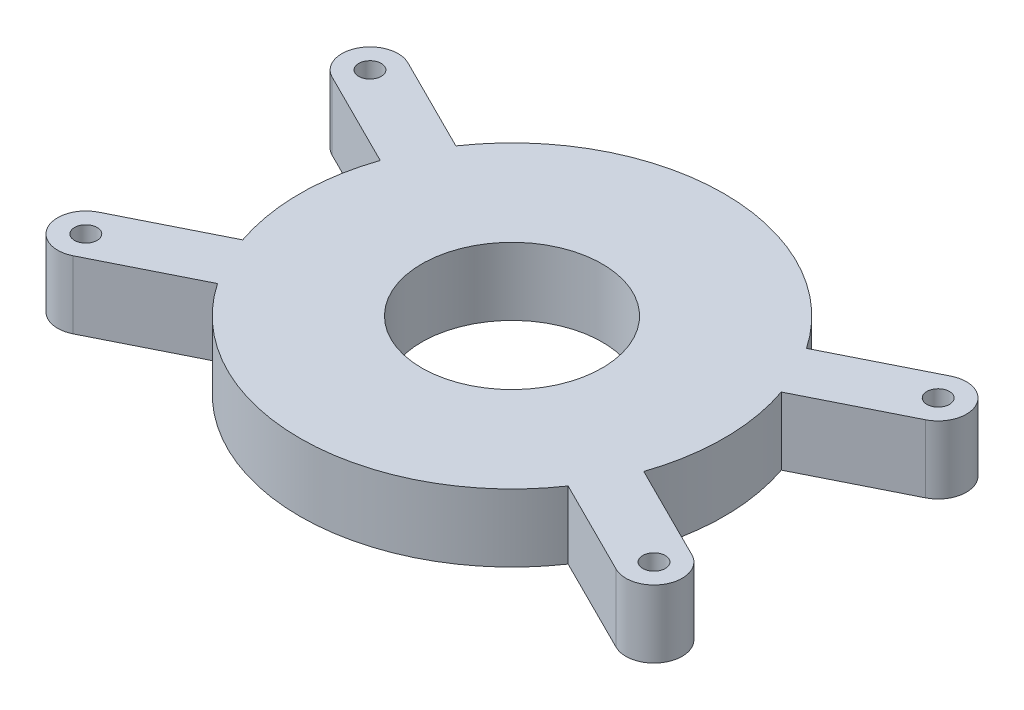
SolidWorks part; units mm, degrees
ref_plane "前视基准面" through (0, 0, 0) normal (0, 0, 1) x (1, 0, 0)
ref_plane "上视基准面" through (0, 0, 0) normal (0, 1, 0) x (1, 0, 0)
ref_plane "右视基准面" through (0, 0, 0) normal (1, 0, 0) x (0, 0, -1)
sketch "草图1" plane through (0, 0, 0) normal (0, 1, 0) x (1, 0, 0)
  line L0 (65.782, 25.9101) -> (44.4585, 15.246)
  line L1 (60.1908, 37.0899) -> (38.8674, 26.4259)
  line L2 (0, 135.0816) -> (0, -134.5462) construction
  line L3 (161.8892, 80.9621) -> (-87.1466, -43.5827) construction
  line L7 (-65.782, 25.9101) -> (-44.4585, 15.246)
  line L8 (-50, 21.5) -> (50, 21.5) construction
  line L9 (-50, 21.5) -> (-50, -21.5) construction
  line L10 (-50, -21.5) -> (50, -21.5) construction
  line L11 (50, 21.5) -> (50, -21.5) construction
  line L12 (-60.1908, 37.0899) -> (-38.8674, 26.4259)
  line L13 (-133.256, 0) -> (145.6129, 0) construction
  line L14 (65.782, -25.9101) -> (44.4585, -15.246)
  line L15 (60.1908, -37.0899) -> (38.8674, -26.4259)
  line L16 (-65.782, -25.9101) -> (-44.4585, -15.246)
  line L17 (-60.1908, -37.0899) -> (-38.8674, -26.4259)
  circle A0 centre (0, 0) radius 20
  circle A1 centre (0, 0) radius 47
  circle A2 centre (62.9864, 31.5) radius 6.25
  circle A6 centre (-62.9864, 31.5) radius 6.25
  circle A7 centre (62.9864, -31.5) radius 6.25
  circle A8 centre (-62.9864, -31.5) radius 6.25
  point P19 (0, 21.5)
  point P20 (50, 0)
  point P41 (0, 0)
  dimension "D2" = 12.5
  dimension "D5" = 94
  dimension "D7" = 40
  dimension "D1" = 63.43
  dimension "D3" = 100
  dimension "D4" = 43
  dimension "D6" = 10
extrude "凸台-拉伸1" add sketch "草图1" along normal blind 15 contours A1 A0 | L12 A6 L7 A1 | A8 L17 A1 L16 | A8 | L15 A7 L14 A1 | A7 | A2 | A2 L1 A1 L0
sketch "草图2" plane through (0, 15, 0) normal (0, 1, 0) x (1, 0, 0)
  line L0 (0, 78.1952) -> (0, -57.2274) construction
  line L1 (-93.9988, 0) -> (82.0699, 0) construction
  circle A0 centre (-62.9864, 31.5) radius 2.5
  arc A1 (-60.1908, 37.0899) -> (-65.782, 25.9101) centre (-62.9864, 31.5) ccw construction
  dimension "D1" = 5
extrude "切除-拉伸1" cut sketch "草图2" against normal blind 5
cosmetic thread "装饰螺纹线1" parameters "D1"=5, "D2"=6
mirror "镜向1" about plane through (0, 0, 0) normal (0, 0, 1) of "切除-拉伸1"
cosmetic thread "装饰螺纹线2" parameters "D1"=5, "D2"=6
mirror "镜向2" about plane through (0, 0, 0) normal (1, 0, 0) of "镜向1", "切除-拉伸1"
cosmetic thread "装饰螺纹线3" parameters "D1"=5, "D2"=6
cosmetic thread "装饰螺纹线4" parameters "D1"=5, "D2"=6
ref_plane "基准面1" through (0, 7.5, 0) normal (0, -1, 0) x (-1, 0, 0)
mirror "镜向3" about plane through (0, 7.5, 0) normal (0, -1, 0) of "镜向2", "切除-拉伸1", "镜向1"
cosmetic thread "装饰螺纹线5" parameters "D1"=5, "D2"=6
cosmetic thread "装饰螺纹线6" parameters "D1"=5, "D2"=6
cosmetic thread "装饰螺纹线7" parameters "D1"=5, "D2"=6
cosmetic thread "装饰螺纹线8" parameters "D1"=5, "D2"=6
